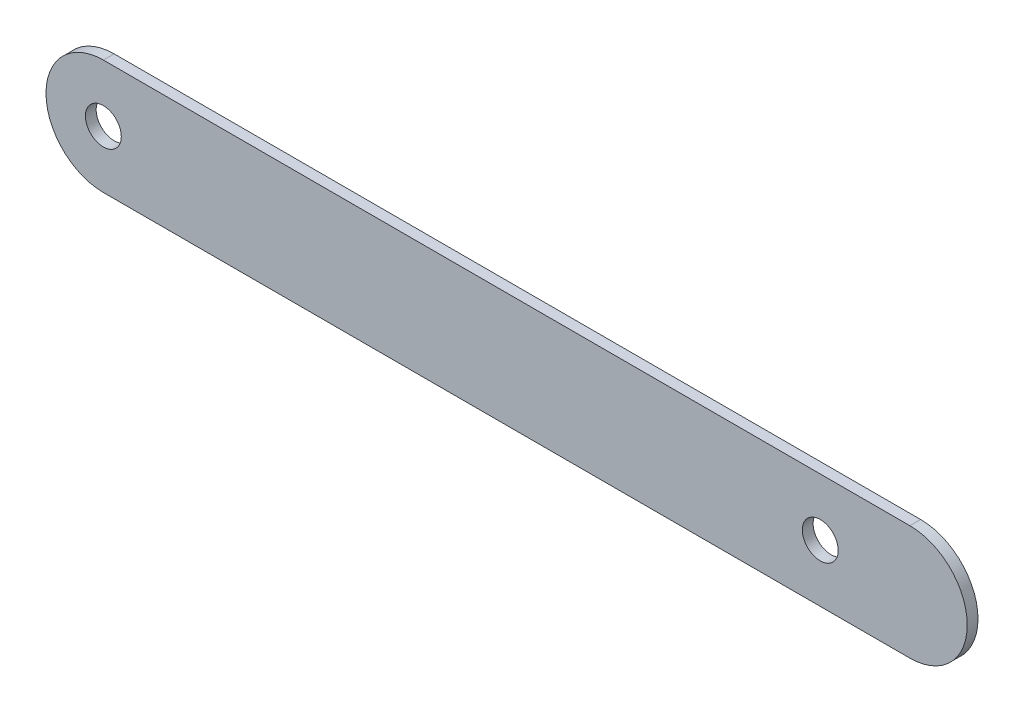
SolidWorks part; units mm, degrees
ref_plane "Front" through (0, 0, 0) normal (0, 0, 1) x (1, 0, 0)
ref_plane "Top" through (0, 0, 0) normal (0, 1, 0) x (1, 0, 0)
ref_plane "Right" through (0, 0, 0) normal (1, 0, 0) x (0, 0, -1)
sketch "草图1" plane through (0, 0, 0) normal (0, 0, 1) x (1, 0, 0)
  line L0 (0, 0) -> (225, 0) construction
  line L1 (0, 16) -> (225, 16)
  line L2 (0, -16) -> (225, -16)
  arc A0 (0, 16) -> (0, -16) centre (0, 0) ccw
  arc A1 (225, -16) -> (225, 16) centre (225, 0) ccw
  circle A2 centre (0, 0) radius 5
  circle A3 centre (200, 0) radius 5
  point P3 (112.5, 0)
  dimension "D1" = 16
  dimension "D3" = 10
  dimension "D4" = 10
  dimension "D2" = 225
  dimension "D5" = 200
extrude "凸台-拉伸1" add sketch "草图1" along normal blind 3
